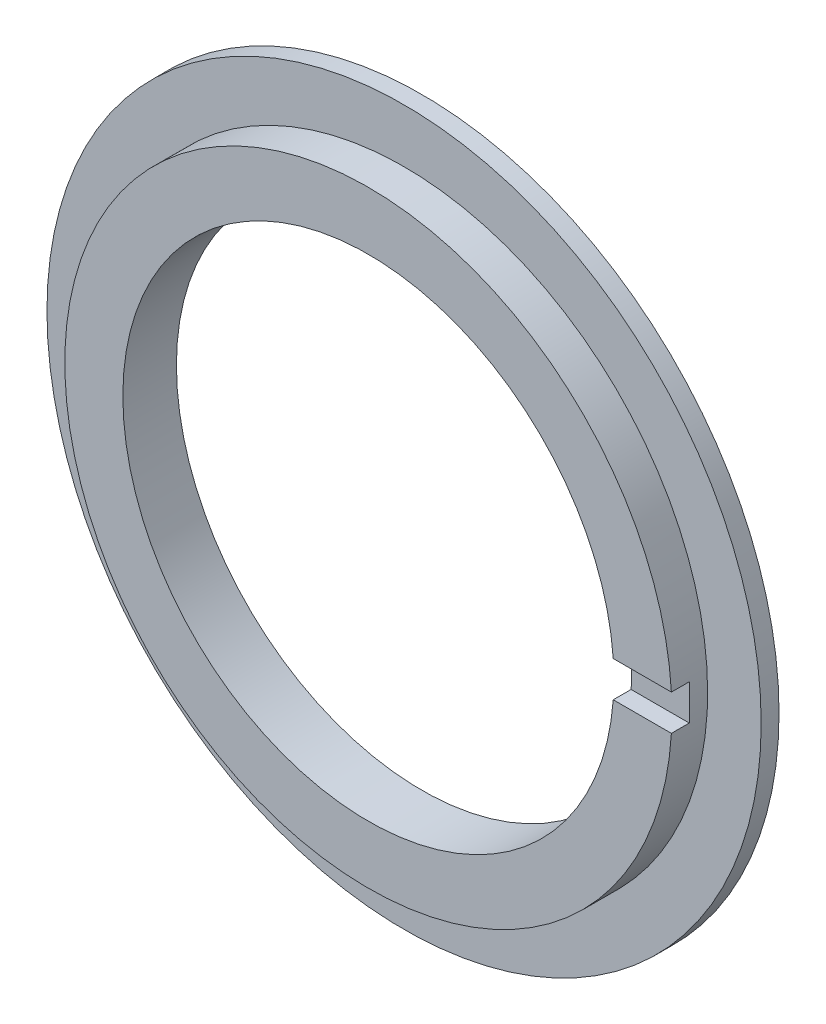
SolidWorks part; units mm, degrees
ref_plane "前视基准面" through (0, 0, 0) normal (0, 0, 1) x (1, 0, 0)
ref_plane "上视基准面" through (0, 0, 0) normal (0, 1, 0) x (1, 0, 0)
ref_plane "右视基准面" through (0, 0, 0) normal (1, 0, 0) x (0, 0, -1)
sketch "草图1" plane through (0, 0, 0) normal (0, 0, 1) x (1, 0, 0)
  circle A0 centre (0, 0) radius 40
  dimension "D1" = 80
extrude "凸台-拉伸1" add sketch "草图1" along normal blind 2
sketch "草图2" plane through (0, 0, 0) normal (0, 0, 1) x (1, 0, 0)
  circle A0 centre (0, 0) radius 34
  dimension "D1" = 68
extrude "凸台-拉伸2" add sketch "草图2" along normal blind 6
sketch "草图3" plane through (0, 0, 6) normal (0, 0, 1) x (1, 0, 0)
  circle A0 centre (0, 0) radius 27.5
  dimension "D1" = 55
extrude "切除-拉伸1" cut sketch "草图3" against normal through all
sketch "草图4" plane through (0, 0, 6) normal (0, 0, 1) x (1, 0, 0)
  line L0 (3.3, 0) -> (-3.3, 0) construction
  line L1 (6.9349, -2) -> (53.8722, -2)
  line L2 (6.9349, -2) -> (6.9349, 2)
  line L3 (6.9349, 2) -> (53.8722, 2)
  line L4 (53.8722, -2) -> (53.8722, 2)
  line L5 (6.9349, -2) -> (53.8722, 2) construction
  line L6 (6.9349, 2) -> (53.8722, -2) construction
  point P0 (30.4035, 0)
  dimension "D1" = 4
extrude "切除-拉伸2" cut sketch "草图4" against normal blind 2
